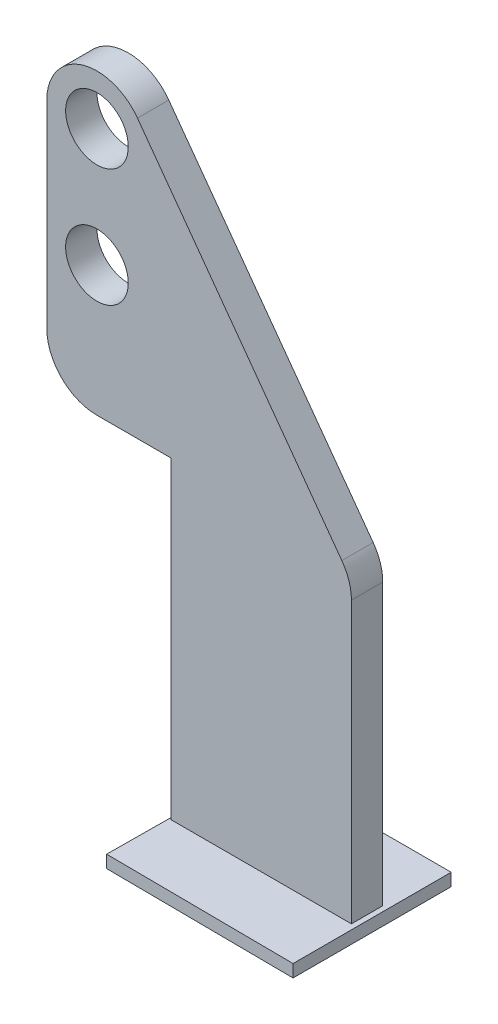
SolidWorks part; units mm, degrees
ref_plane "Front Plane" through (0, 0, 0) normal (0, 0, 1) x (1, 0, 0)
ref_plane "Top Plane" through (0, 0, 0) normal (0, 1, 0) x (1, 0, 0)
ref_plane "Right Plane" through (0, 0, 0) normal (1, 0, 0) x (0, 0, -1)
sketch "Sketch1" plane through (0, 0, 0) normal (0, 0, 1) x (1, 0, 0)
  line L4 (6.9248, -0.1388) -> (-1.3616, 11.2549)
  line L5 (-5.0369, 10.0598) -> (-5.0369, 2.032)
  line L6 (-3.0049, 0) -> (0, 0)
  line L7 (0, 0) -> (0, -12.7)
  line L8 (0, -12.7) -> (7.3134, -12.7)
  line L9 (7.3134, -12.7) -> (7.3134, -1.334)
  line L10 (-3.0049, 10.0598) -> (-3.0049, -2.9384) construction
  circle A0 centre (-3.0049, 10.0598) radius 1.27
  arc A1 (-5.0369, 2.032) -> (-3.0049, 0) centre (-3.0049, 2.032) ccw
  arc A2 (7.3134, -1.334) -> (6.9248, -0.1388) centre (5.2814, -1.334) ccw
  arc A3 (-1.3616, 11.2549) -> (-5.0369, 10.0598) centre (-3.0049, 10.0598) ccw
  circle A4 centre (-3.0049, 5.274) radius 1.27
  dimension "D1" = 2.54
  dimension "D2" = 2.032
  dimension "D4" = 2.54
  dimension "D3" = 12.7
extrude "Boss-Extrude1" add sketch "Sketch1" along normal blind 1.27
ref_plane "Plane1" through (0, -12.7, 0) normal (0, -1, 0) x (-1, 0, 0)
sketch "Sketch2" plane through (0, -12.7, 0) normal (0, -1, 0) x (-1, 0, 0)
  line L0 (-7.5232, 2.5649) -> (-7.5232, -3.8463)
  line L1 (-7.5232, -3.8463) -> (0.0968, -3.7851)
  line L2 (0.0968, -3.7851) -> (0.0458, 2.5649)
  line L3 (0.0458, 2.5649) -> (-7.5232, 2.5649)
  point P11 (0, 0)
  dimension "D1" = 6.35
  dimension "D2" = 7.62
extrude "Boss-Extrude2" add sketch "Sketch2" along normal blind 0.508
